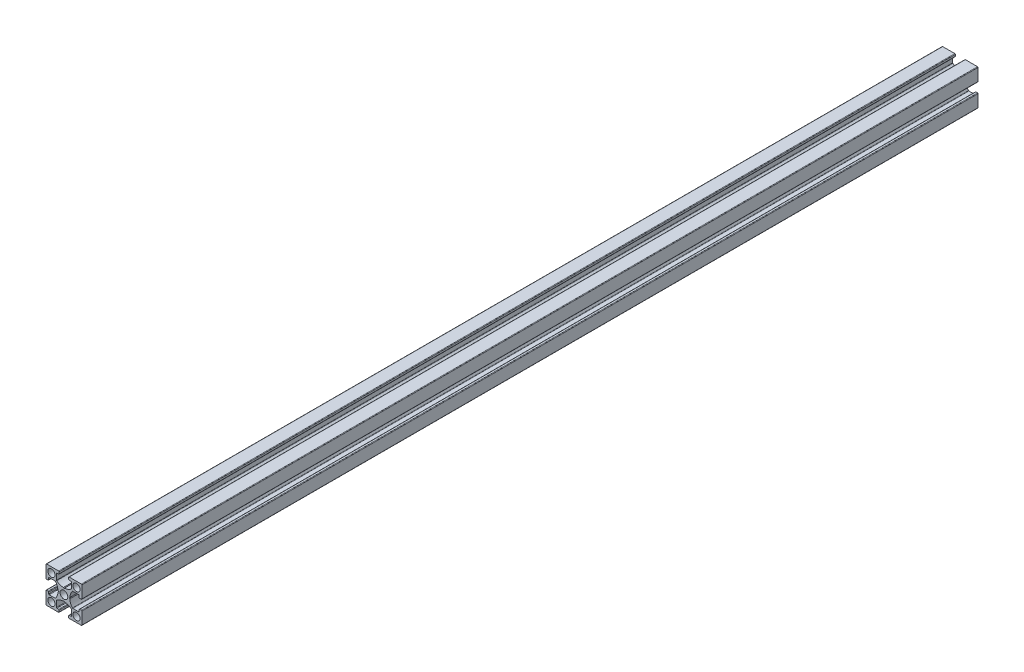
SolidWorks part; units mm, degrees
ref_plane "정면" through (0, 0, 0) normal (0, 0, 1) x (1, 0, 0)
ref_plane "윗면" through (0, 0, 0) normal (0, 1, 0) x (1, 0, 0)
ref_plane "우측면" through (0, 0, 0) normal (1, 0, 0) x (0, 0, -1)
sketch "Model" plane through (0, 0, 0) normal (0, 0, 1) x (1, 0, 0)
  line L0 (2292.4151, 1187.1915) -> (2314.8128, 1187.1915) construction
  line L1 (2307.7639, 1192.1343) -> (2307.7639, 1195.3915)
  line L2 (2307.4639, 1195.6915) -> (2306.5639, 1195.6915)
  line L3 (2306.2639, 1195.9915) -> (2306.2639, 1196.8915)
  line L4 (2306.5639, 1197.1915) -> (2313.3139, 1197.1915)
  line L5 (2313.6139, 1196.8915) -> (2313.6139, 1190.1415)
  line L6 (2313.3139, 1189.8415) -> (2312.4139, 1189.8415)
  line L7 (2312.1139, 1190.1415) -> (2312.1139, 1191.0415)
  line L8 (2311.8139, 1191.3415) -> (2308.5567, 1191.3415)
  line L9 (2306.9212, 1187.4988) -> (2306.6139, 1187.1915)
  line L10 (2306.6139, 1187.1915) -> (2306.9212, 1186.8843)
  line L11 (2308.5567, 1183.0415) -> (2311.8139, 1183.0415)
  line L12 (2312.1139, 1183.3415) -> (2312.1139, 1184.2415)
  line L13 (2312.4139, 1184.5415) -> (2313.3139, 1184.5415)
  line L14 (2313.6139, 1184.2415) -> (2313.6139, 1177.4915)
  line L15 (2313.3139, 1177.1915) -> (2306.5639, 1177.1915)
  line L16 (2306.2639, 1177.4915) -> (2306.2639, 1178.3915)
  line L17 (2306.5639, 1178.6915) -> (2307.4639, 1178.6915)
  line L18 (2307.7639, 1178.9915) -> (2307.7639, 1182.2488)
  line L19 (2303.9212, 1183.8843) -> (2303.6139, 1184.1915)
  line L20 (2303.6139, 1184.1915) -> (2303.3066, 1183.8843)
  line L21 (2299.4639, 1182.2488) -> (2299.4639, 1178.9915)
  line L22 (2299.7639, 1178.6915) -> (2300.6639, 1178.6915)
  line L23 (2300.9639, 1178.3915) -> (2300.9639, 1177.4915)
  line L24 (2300.6639, 1177.1915) -> (2293.9139, 1177.1915)
  line L25 (2293.6139, 1177.4915) -> (2293.6139, 1184.2415)
  line L26 (2293.9139, 1184.5415) -> (2294.8139, 1184.5415)
  line L27 (2295.1139, 1184.2415) -> (2295.1139, 1183.3415)
  line L28 (2295.4139, 1183.0415) -> (2298.6712, 1183.0415)
  line L29 (2300.3066, 1186.8843) -> (2300.6139, 1187.1915)
  line L30 (2300.6139, 1187.1915) -> (2300.3066, 1187.4988)
  line L31 (2298.6712, 1191.3415) -> (2295.4139, 1191.3415)
  line L32 (2295.1139, 1191.0415) -> (2295.1139, 1190.1415)
  line L33 (2294.8139, 1189.8415) -> (2293.9139, 1189.8415)
  line L34 (2293.6139, 1190.1415) -> (2293.6139, 1196.8915)
  line L35 (2293.9139, 1197.1915) -> (2300.6639, 1197.1915)
  line L36 (2300.9639, 1196.8915) -> (2300.9639, 1195.9915)
  line L37 (2300.6639, 1195.6915) -> (2299.7639, 1195.6915)
  line L38 (2299.4639, 1195.3915) -> (2299.4639, 1192.1343)
  line L39 (2303.3066, 1190.4988) -> (2303.6139, 1190.1915)
  line L40 (2303.6139, 1190.1915) -> (2303.9212, 1190.4988)
  line L41 (2294.1139, 1194.1915) -> (2299.1139, 1194.1915) construction
  line L42 (2296.6139, 1196.6915) -> (2296.6139, 1191.6915) construction
  line L43 (2294.1139, 1180.1915) -> (2299.1139, 1180.1915) construction
  line L44 (2296.6139, 1177.6915) -> (2296.6139, 1182.6915) construction
  line L45 (2303.6139, 1198.3904) -> (2303.6139, 1175.9927) construction
  line L46 (2313.1139, 1194.1915) -> (2308.1139, 1194.1915) construction
  line L47 (2310.6139, 1196.6915) -> (2310.6139, 1191.6915) construction
  line L48 (2310.6139, 1177.6915) -> (2310.6139, 1182.6915) construction
  line L49 (2313.1139, 1180.1915) -> (2308.1139, 1180.1915) construction
  circle A0 centre (2303.6139, 1187.1915) radius 2.15
  circle A1 centre (2296.6139, 1194.1915) radius 2
  circle A2 centre (2296.6139, 1180.1915) radius 2
  circle A3 centre (2310.6139, 1194.1915) radius 2
  circle A4 centre (2310.6139, 1180.1915) radius 2
  arc A5 (2307.7639, 1195.3915) -> (2307.4639, 1195.6915) centre (2307.4639, 1195.3915) ccw
  arc A6 (2306.2639, 1195.9915) -> (2306.5639, 1195.6915) centre (2306.5639, 1195.9915) ccw
  arc A7 (2306.5639, 1197.1915) -> (2306.2639, 1196.8915) centre (2306.5639, 1196.8915) ccw
  arc A8 (2313.6139, 1196.8915) -> (2313.3139, 1197.1915) centre (2313.3139, 1196.8915) ccw
  arc A9 (2313.3139, 1189.8415) -> (2313.6139, 1190.1415) centre (2313.3139, 1190.1415) ccw
  arc A10 (2312.1139, 1190.1415) -> (2312.4139, 1189.8415) centre (2312.4139, 1190.1415) ccw
  arc A11 (2312.1139, 1191.0415) -> (2311.8139, 1191.3415) centre (2311.8139, 1191.0415) ccw
  arc A12 (2308.5567, 1191.3415) -> (2308.3217, 1191.2281) centre (2308.5567, 1191.0415) ccw
  arc A13 (2308.3217, 1191.2281) -> (2306.9212, 1187.4988) centre (2313.4048, 1187.1915) ccw
  arc A14 (2306.9212, 1186.8843) -> (2308.3217, 1183.155) centre (2313.4048, 1187.1915) ccw
  arc A15 (2308.3217, 1183.155) -> (2308.5567, 1183.0415) centre (2308.5567, 1183.3415) ccw
  arc A16 (2311.8139, 1183.0415) -> (2312.1139, 1183.3415) centre (2311.8139, 1183.3415) ccw
  arc A17 (2312.4139, 1184.5415) -> (2312.1139, 1184.2415) centre (2312.4139, 1184.2415) ccw
  arc A18 (2313.6139, 1184.2415) -> (2313.3139, 1184.5415) centre (2313.3139, 1184.2415) ccw
  arc A19 (2313.3139, 1177.1915) -> (2313.6139, 1177.4915) centre (2313.3139, 1177.4915) ccw
  arc A20 (2306.2639, 1177.4915) -> (2306.5639, 1177.1915) centre (2306.5639, 1177.4915) ccw
  arc A21 (2306.5639, 1178.6915) -> (2306.2639, 1178.3915) centre (2306.5639, 1178.3915) ccw
  arc A22 (2307.4639, 1178.6915) -> (2307.7639, 1178.9915) centre (2307.4639, 1178.9915) ccw
  arc A23 (2307.7639, 1182.2488) -> (2307.6505, 1182.4837) centre (2307.4639, 1182.2488) ccw
  arc A24 (2307.6505, 1182.4837) -> (2303.9212, 1183.8843) centre (2303.6139, 1177.4007) ccw
  arc A25 (2303.3066, 1183.8843) -> (2299.5774, 1182.4837) centre (2303.6139, 1177.4007) ccw
  arc A26 (2299.5774, 1182.4837) -> (2299.4639, 1182.2488) centre (2299.7639, 1182.2488) ccw
  arc A27 (2299.4639, 1178.9915) -> (2299.7639, 1178.6915) centre (2299.7639, 1178.9915) ccw
  arc A28 (2300.9639, 1178.3915) -> (2300.6639, 1178.6915) centre (2300.6639, 1178.3915) ccw
  arc A29 (2300.6639, 1177.1915) -> (2300.9639, 1177.4915) centre (2300.6639, 1177.4915) ccw
  arc A30 (2293.6139, 1177.4915) -> (2293.9139, 1177.1915) centre (2293.9139, 1177.4915) ccw
  arc A31 (2293.9139, 1184.5415) -> (2293.6139, 1184.2415) centre (2293.9139, 1184.2415) ccw
  arc A32 (2295.1139, 1184.2415) -> (2294.8139, 1184.5415) centre (2294.8139, 1184.2415) ccw
  arc A33 (2295.1139, 1183.3415) -> (2295.4139, 1183.0415) centre (2295.4139, 1183.3415) ccw
  arc A34 (2298.6712, 1183.0415) -> (2298.9061, 1183.155) centre (2298.6712, 1183.3415) ccw
  arc A35 (2298.9061, 1183.155) -> (2300.3066, 1186.8843) centre (2293.8231, 1187.1915) ccw
  arc A36 (2300.3066, 1187.4988) -> (2298.9061, 1191.2281) centre (2293.8231, 1187.1915) ccw
  arc A37 (2298.9061, 1191.2281) -> (2298.6712, 1191.3415) centre (2298.6712, 1191.0415) ccw
  arc A38 (2295.4139, 1191.3415) -> (2295.1139, 1191.0415) centre (2295.4139, 1191.0415) ccw
  arc A39 (2294.8139, 1189.8415) -> (2295.1139, 1190.1415) centre (2294.8139, 1190.1415) ccw
  arc A40 (2293.6139, 1190.1415) -> (2293.9139, 1189.8415) centre (2293.9139, 1190.1415) ccw
  arc A41 (2293.9139, 1197.1915) -> (2293.6139, 1196.8915) centre (2293.9139, 1196.8915) ccw
  arc A42 (2300.9639, 1196.8915) -> (2300.6639, 1197.1915) centre (2300.6639, 1196.8915) ccw
  arc A43 (2300.6639, 1195.6915) -> (2300.9639, 1195.9915) centre (2300.6639, 1195.9915) ccw
  arc A44 (2299.7639, 1195.6915) -> (2299.4639, 1195.3915) centre (2299.7639, 1195.3915) ccw
  arc A45 (2299.4639, 1192.1343) -> (2299.5774, 1191.8994) centre (2299.7639, 1192.1343) ccw
  arc A46 (2299.5774, 1191.8994) -> (2303.3066, 1190.4988) centre (2303.6139, 1196.9824) ccw
  arc A47 (2303.9212, 1190.4988) -> (2307.6505, 1191.8994) centre (2303.6139, 1196.9824) ccw
  arc A48 (2307.6505, 1191.8994) -> (2307.7639, 1192.1343) centre (2307.4639, 1192.1343) ccw
extrude "보스-돌출1" add sketch "Model" along normal blind 500
